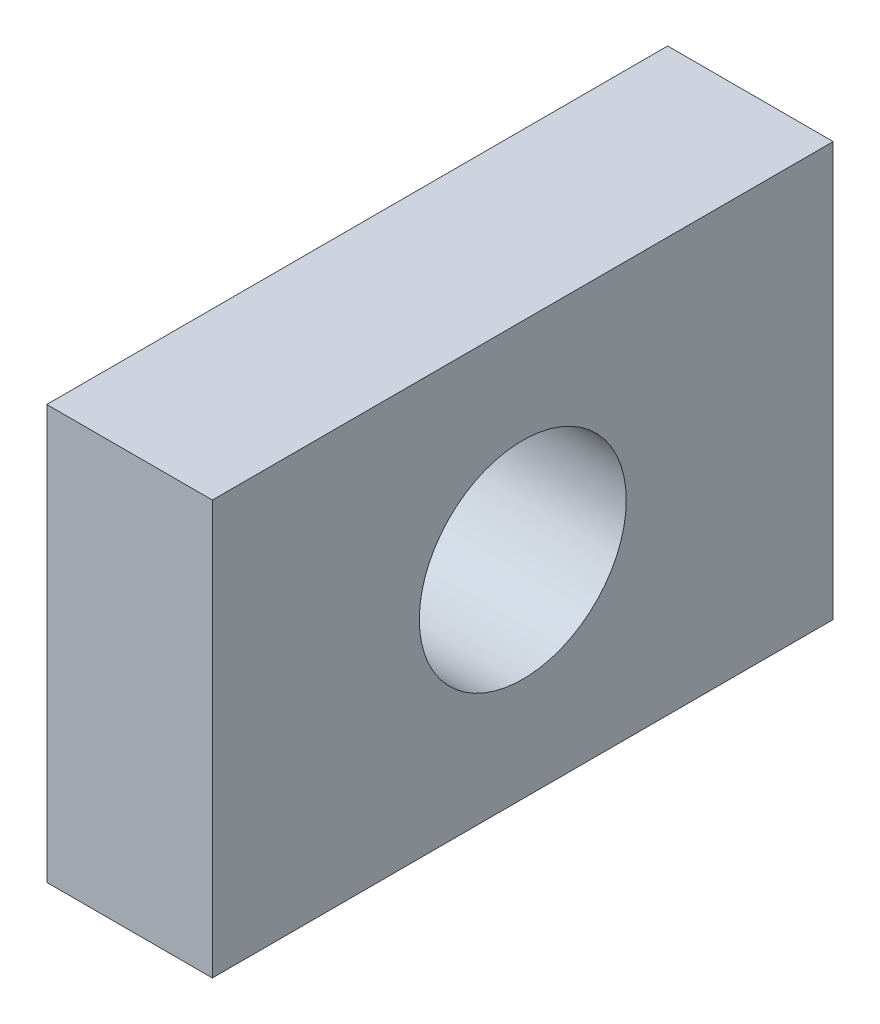
SolidWorks part; units mm, degrees
ref_plane "Front Plane" through (0, 0, 0) normal (0, 0, 1) x (1, 0, 0)
ref_plane "Top Plane" through (0, 0, 0) normal (0, 1, 0) x (1, 0, 0)
ref_plane "Right Plane" through (0, 0, 0) normal (1, 0, 0) x (0, 0, -1)
sketch "Sketch1" plane through (0, 0, 0) normal (1, 0, 0) x (0, 0, -1)
  line L1 (75, -50) -> (-75, -50)
  line L2 (75, -50) -> (75, 50)
  line L3 (75, 50) -> (-75, 50)
  line L4 (-75, -50) -> (-75, 50)
  line L5 (75, -50) -> (-75, 50) construction
  line L6 (75, 50) -> (-75, -50) construction
  circle A0 centre (0, 0) radius 25
  point P0 (0, 0)
  dimension "D1" = 150
  dimension "D2" = 100
extrude "Boss-Extrude1" add sketch "Sketch1" along normal blind 40
